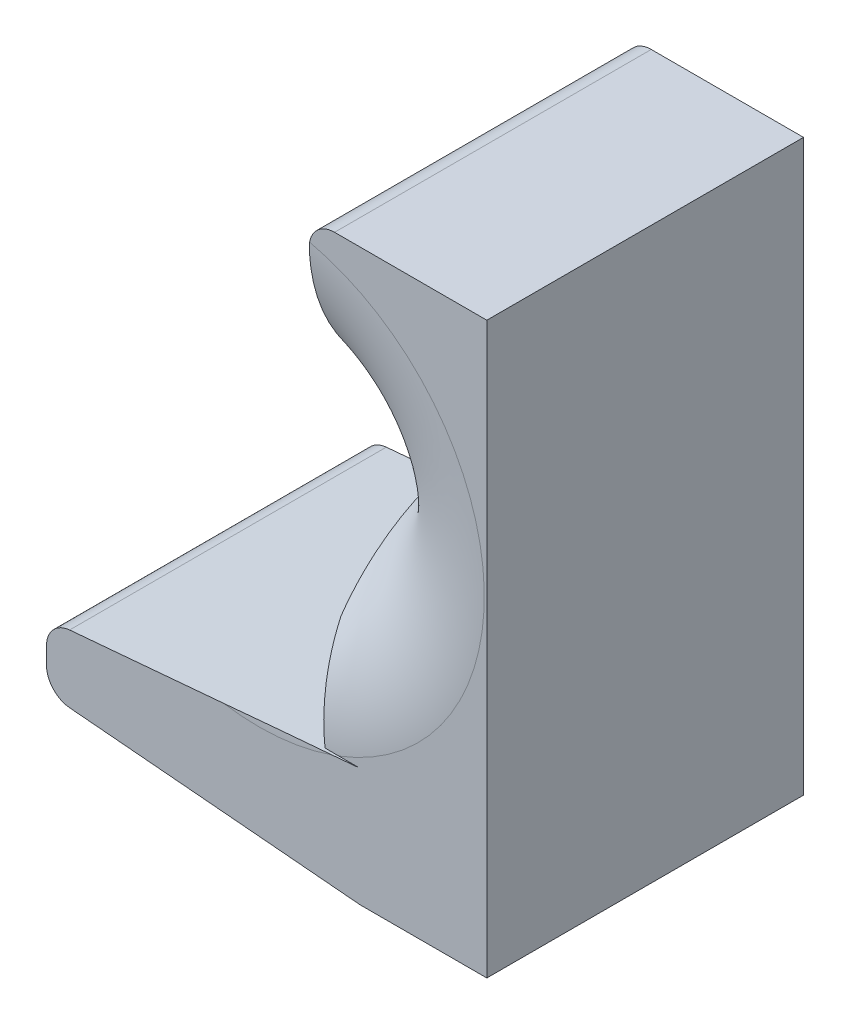
SolidWorks part; units mm, degrees
ref_plane "Front Plane" through (0, 0, 0) normal (0, 0, 1) x (1, 0, 0)
ref_plane "Top Plane" through (0, 0, 0) normal (0, 1, 0) x (1, 0, 0)
ref_plane "Right Plane" through (0, 0, 0) normal (1, 0, 0) x (0, 0, -1)
sketch "finger" plane through (0, 0, 0) normal (0, 0, 1) x (1, 0, 0)
  line L0 (0, 0) -> (5.0161, 13.7815) construction
  line L1 (5.0161, 13.7815) -> (5.0161, 28.518) construction
  line L2 (0, 0) -> (-3.1472, -35.9726)
  line L3 (-3.1472, -35.9726) -> (12.6257, -49.2076)
  line L4 (12.6257, -49.2076) -> (29.8674, -44.5877)
  line L5 (28.638, -39.9995) -> (11.3963, -44.6194)
  line L6 (10.1669, -40.0313) -> (27.4087, -35.4114)
  line L7 (10.1669, -40.0313) -> (11.3963, -44.6194)
  line L8 (11.3963, -44.6194) -> (12.6257, -49.2076)
  line L9 (28.638, -39.9995) -> (33.2262, -38.7701) construction
  circle A0 centre (28.638, -39.9995) radius 4.75
  dimension "D3" = 15
  dimension "D4" = 55
  dimension "D5" = 20
  dimension "D6" = 55
  dimension "D7" = 36.11
  dimension "D8" = 20.59
  dimension "D2" = 9.5
  dimension "D1" = 22.6
ref_plane "est_lift_plane" through (28.638, 0, 0) normal (1, 0, 0) x (0, 0, -1)
sketch "Sketch2" plane through (0, 0, 0) normal (0, 0, 1) x (1, 0, 0)
  line L0 (25.388, -29.2495) -> (25.388, -26.2495) construction
  line L1 (25.388, -26.2495) -> (25.388, -25.4495) construction
  line L2 (25.388, -29.2495) -> (25.388, -29.1495) construction
  line L3 (25.388, -29.1495) -> (25.388, -29.1245) construction
  line L4 (29.368, -34.2495) -> (33.388, -34.2495) construction
  line L5 (25.388, -30.7495) -> (33.388, -30.7495) construction
  line L6 (25.388, -35.2495) -> (33.388, -35.2495) construction
  line L7 (29.368, -34.2495) -> (29.368, -35.2495)
  line L8 (29.368, -34.2495) -> (29.368, -11.7495)
  line L9 (29.368, -11.7495) -> (43.388, -11.7495)
  line L10 (43.388, -11.7495) -> (43.388, -56.724)
  line L12 (8.6257, -54.5575) -> (8.6257, -49.5575)
  line L13 (8.6257, -49.5575) -> (33.388, -47.3911)
  line L14 (33.388, -47.3911) -> (33.388, -35.2495)
  line L15 (12.6257, -49.2076) -> (12.6257, -54.9075)
  line L16 (8.6257, -52.0575) -> (12.6257, -52.0575)
  line L17 (25.388, -29.2495) -> (25.388, -29.1245) construction
  line L18 (1.0853, 18.3368) -> (15.1054, 18.3368) construction
  line L19 (-25.8903, -11.4233) -> (-21.8903, -11.4233) construction
  line L20 (-25.8903, -13.9233) -> (-25.8903, -8.9233) construction
  line L21 (-2.4854, 5.3476) -> (5.5146, 5.3476) construction
  line L22 (1.0853, 1.8476) -> (5.1054, 1.8476) construction
  line L23 (29.368, -35.2495) -> (29.368, -47.7495) construction
  line L24 (25.388, -30.7495) -> (25.388, -47.7495) construction
  line L25 (25.388, -30.7495) -> (25.388, -13.7495) construction
  line L26 (25.388, -13.7495) -> (25.388, -11.7495) construction
  line L27 (-2.4854, 18.3368) -> (-2.4854, 16.3368) construction
  line L28 (29.368, -35.2495) -> (33.388, -35.2495)
  line L30 (8.6257, -54.5575) -> (33.388, -56.724)
  line L34 (33.388, -56.724) -> (43.388, -56.724)
  line L35 (0, 0) -> (8, 0) construction
  line L37 (3.9799, -3.5) -> (3.9799, -4.5) construction
  line L38 (-23.405, -20.4436) -> (-23.405, -15.4436) construction
  line L39 (-23.405, -17.9436) -> (-19.405, -17.9436) construction
  line L40 (0, 12.8193) -> (0, 10.8193) construction
  circle A0 centre (25.388, -30.7495) radius 5.3 construction
  circle A1 centre (25.388, -30.7495) radius 4.5 construction
  circle A2 centre (25.388, -30.7495) radius 1.5 construction
  circle A3 centre (25.388, -30.7495) radius 1.6 construction
  circle A4 centre (25.388, -30.7495) radius 1.625 construction
  circle A6 centre (-2.4854, 5.3476) radius 4.5 construction
  circle A7 centre (-2.4854, 5.3476) radius 1.625 construction
  circle A9 centre (0, 0) radius 5.3 construction
  circle A10 centre (-2.4854, 5.3476) radius 1.6 construction
  circle A11 centre (-2.4854, 5.3476) radius 1.5 construction
  circle A12 centre (28.638, -39.9995) radius 4.75 construction
  circle A13 centre (0, 0) radius 4.5 construction
  dimension "D2" = 5
  dimension "D1" = 12.5
  dimension "D3" = 10
extrude "Boss-Extrude1" add sketch "Sketch2" along normal mid plane 25
sketch "Sketch4" plane through (33.388, 0, 0) normal (-1, 0, 0) x (0, 0, 1)
  line L0 (0, -19.1193) -> (0, 19.1193) construction
  line L1 (-12.5, -47.7495) -> (-12.5, -35.2495)
  line L2 (-12.5, -35.2495) -> (12.5, -35.2495)
  line L3 (12.5, -35.2495) -> (12.5, -47.7495)
  circle A0 centre (0, -47.7495) radius 12.5 construction
  arc A1 (-12.5, -47.7495) -> (12.5, -47.7495) centre (0, -47.7495) cw
  line M4 (-12.5, -35.2495) -> (-12.5, -47.3911)
  line M6 (12.5, -47.3911) -> (12.5, -35.2495)
  line M7 (12.5, -35.2495) -> (-12.5, -35.2495)
extrude "Boss-Extrude2" add sketch "Sketch4" along normal up to surface (4.0201 mm away) contours A1 L2 M4 | A1 M7 M6
ref_plane "roller_plane" through (25.388, 0, 0) normal (-1, 0, 0) x (0, 0, 1)
sketch "Sketch3" plane through (25.388, 0, 0) normal (-1, 0, 0) x (0, 0, 1)
  line L0 (0, -19.1193) -> (0, 19.1193) construction
  line L1 (0, 0) -> (0, -35.9726) construction
  line L2 (-12.5, -30.7495) -> (12.5, -30.7495)
  line L3 (-12.5, -47.3911) -> (-12.5, -11.7495) construction
  line L4 (12.5, -11.7495) -> (12.5, -47.3911) construction
  line L5 (-12.5, -30.7495) -> (-12.5, -12.9495)
  line L6 (12.5, -30.7495) -> (12.5, -12.9495)
  circle A0 centre (0, -12.9495) radius 12.5 construction
  arc A1 (-12.5, -12.9495) -> (12.5, -12.9495) centre (0, -12.9495) ccw
revolve "Cut-Revolve1" cut sketch "Sketch3" angle 360 about L2
fillet "Fillet2" radius 2 3 edges at (29.368, -11.7495, 0) (8.6257, -49.5575, 0) (8.6257, -54.5575, 0)
equation "\"depth\"= 8.5"
equation "\"width\"= 25"
equation "\"distal\"= 22.6"
equation "\"proximal\"= 36.11"
equation "\"medial\"= 20.59"
equation "\"h_offset\"= 0"
equation "\"l_offset\"= 0"
equation "\"D7@finger\" = \"proximal\""
equation "\"D8@finger\" = \"medial\""
equation "\"D1@Boss-Extrude1\"=\"width\""
equation "\"D1@finger\"=\"distal\""
equation "\"D1@Sketch2\"=\"width\"/2"
